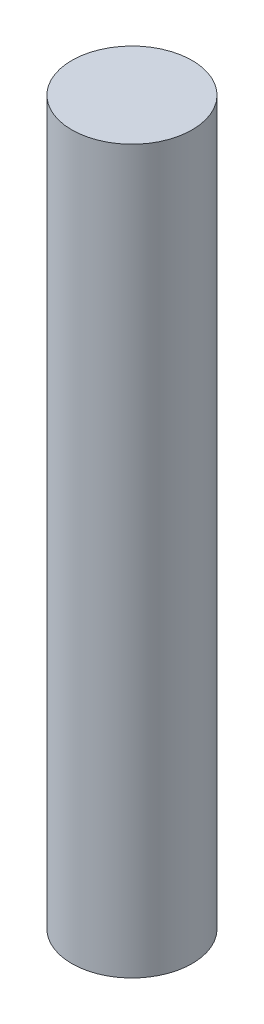
SolidWorks part; units mm, degrees
ref_plane "前视基准面" through (0, 0, 0) normal (0, 0, 1) x (1, 0, 0)
ref_plane "上视基准面" through (0, 0, 0) normal (0, 1, 0) x (1, 0, 0)
ref_plane "右视基准面" through (0, 0, 0) normal (1, 0, 0) x (0, 0, -1)
other "Configuration Table"
sketch "草图1" plane through (0, 0, 0) normal (0, 1, 0) x (1, 0, 0)
  circle A0 centre (0, 0) radius 2
extrude "凸台-拉伸1" add sketch "草图1" along normal blind 24
